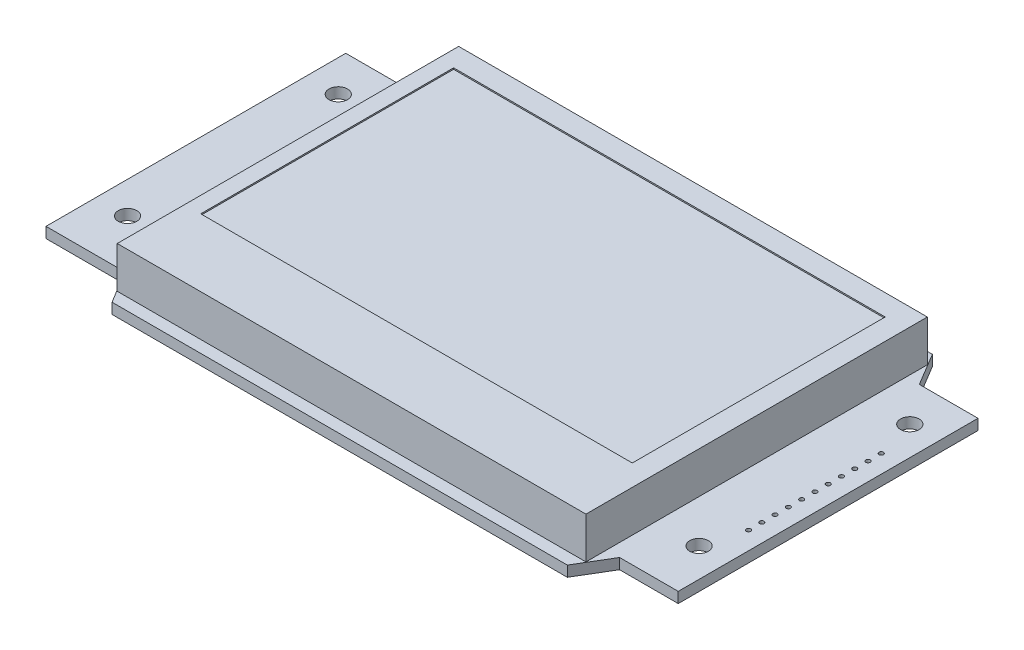
SolidWorks part; units mm, degrees
ref_plane "Front Plane" through (0, 0, 0) normal (0, 0, 1) x (1, 0, 0)
ref_plane "Top Plane" through (0, 0, 0) normal (0, 1, 0) x (1, 0, 0)
ref_plane "Right Plane" through (0, 0, 0) normal (1, 0, 0) x (0, 0, -1)
sketch "Sketch1" plane through (0, 0, 0) normal (0, 1, 0) x (1, 0, 0)
  line L0 (-60.0596, 21.17) -> (-60.0596, -23.9912)
  line L1 (35.1904, 21.17) -> (35.1904, -23.9912)
  line L2 (-45.1752, 26.0849) -> (23.4048, 26.0849)
  line L3 (-45.1752, -28.9151) -> (23.4048, -28.9151)
  line L4 (-60.0596, -1.4106) -> (35.1904, -1.4106) construction
  line L5 (-60.0596, -23.9912) -> (-48.2232, -23.9912)
  line L6 (-60.0596, 21.17) -> (-48.2232, 21.17)
  line L7 (35.1904, 21.17) -> (26.3512, 21.17)
  line L8 (35.1904, -23.9912) -> (26.3512, -23.9912)
  line L9 (-10.8852, 26.0849) -> (-10.8852, -28.9151) construction
  line L10 (-48.2232, -23.9912) -> (-45.1752, -28.9151)
  line L11 (26.3512, -23.9912) -> (23.4048, -28.9151)
  line L12 (23.4048, 26.0849) -> (26.3512, 21.17)
  line L13 (-45.1752, 26.0849) -> (-48.2232, 21.17)
  dimension "D1" = 45.1612
  dimension "D2" = 55
  dimension "D3" = 27.4955
  dimension "D4" = 11.8364
  dimension "D5" = 8.8392
  dimension "D6" = 11.7856
  dimension "D7" = 95.25
  dimension "D8" = 68.58
extrude "Boss-Extrude1" add sketch "Sketch1" along normal blind 1.6
sketch "Sketch2" plane through (0, 1.6, 0) normal (0, 1, 0) x (1, 0, 0)
  line L0 (35.1904, -23.9912) -> (35.1904, 21.17) construction
  line L1 (26.3512, -23.9912) -> (35.1904, -23.9912) construction
  circle A0 centre (-55.2717, 15.2518) radius 1.397
  circle A1 centre (-55.2717, -16.4982) radius 1.397
  circle A2 centre (30.8343, -16.4982) radius 1.397
  circle A3 centre (30.8343, 15.2518) radius 1.397
  dimension "D1" = 2.794
  dimension "D2" = 31.75
  dimension "D3" = 86.106
  dimension "D4" = 4.3561
  dimension "D5" = 7.493
extrude "Cut-Extrude1" cut sketch "Sketch2" against normal through all
sketch "Sketch3" plane through (0, 1.6, 0) normal (0, 1, 0) x (1, 0, 0)
  line L0 (23.4048, 26.0849) -> (-45.1752, 26.0849) construction
  line L1 (-46.2166, 24.3349) -> (24.3954, 24.3349)
  line L2 (-46.2166, 24.3349) -> (-46.2166, -27.1001)
  line L3 (-46.2166, -27.1001) -> (24.3954, -27.1001)
  line L4 (24.3954, 24.3349) -> (24.3954, -27.1001)
  line L5 (35.1904, -23.9912) -> (35.1904, 21.17) construction
  dimension "D1" = 51.435
  dimension "D2" = 70.612
  dimension "D3" = 1.75
  dimension "D4" = 10.795
extrude "Boss-Extrude2" add sketch "Sketch3" along normal blind 6.2357
sketch "Sketch4" plane through (0, 7.8357, 0) normal (0, 1, 0) x (1, 0, 0)
  line L0 (-46.2166, -27.1001) -> (24.3954, -27.1001) construction
  line L1 (-43.8036, 21.1599) -> (21.2204, 21.1599)
  line L2 (-43.8036, 21.1599) -> (-43.8036, -16.9401)
  line L3 (-43.8036, -16.9401) -> (21.2204, -16.9401)
  line L4 (21.2204, 21.1599) -> (21.2204, -16.9401)
  line L5 (-46.2166, 24.3349) -> (-46.2166, -27.1001) construction
  dimension "D1" = 38.1
  dimension "D2" = 65.024
  dimension "D3" = 10.16
  dimension "D4" = 2.413
extrude "Cut-Extrude2" cut sketch "Sketch4" against normal blind 0.2
sketch "Sketch5" plane through (0, 1.6, 0) normal (0, 1, 0) x (1, 0, 0)
  line L0 (35.1904, -23.9912) -> (35.1904, 21.17) construction
  line L1 (35.1904, 21.17) -> (26.3512, 21.17) construction
  circle A0 centre (32.4904, 9.3) radius 0.3302
  dimension "D1" = 0.6604
  dimension "D2" = 2.7
  dimension "D3" = 11.87
extrude "Cut-Extrude3" cut sketch "Sketch5" against normal through all
pattern_linear "LPattern1" count 11 spacing 2 along (0, 0, 1) of "Cut-Extrude3"
